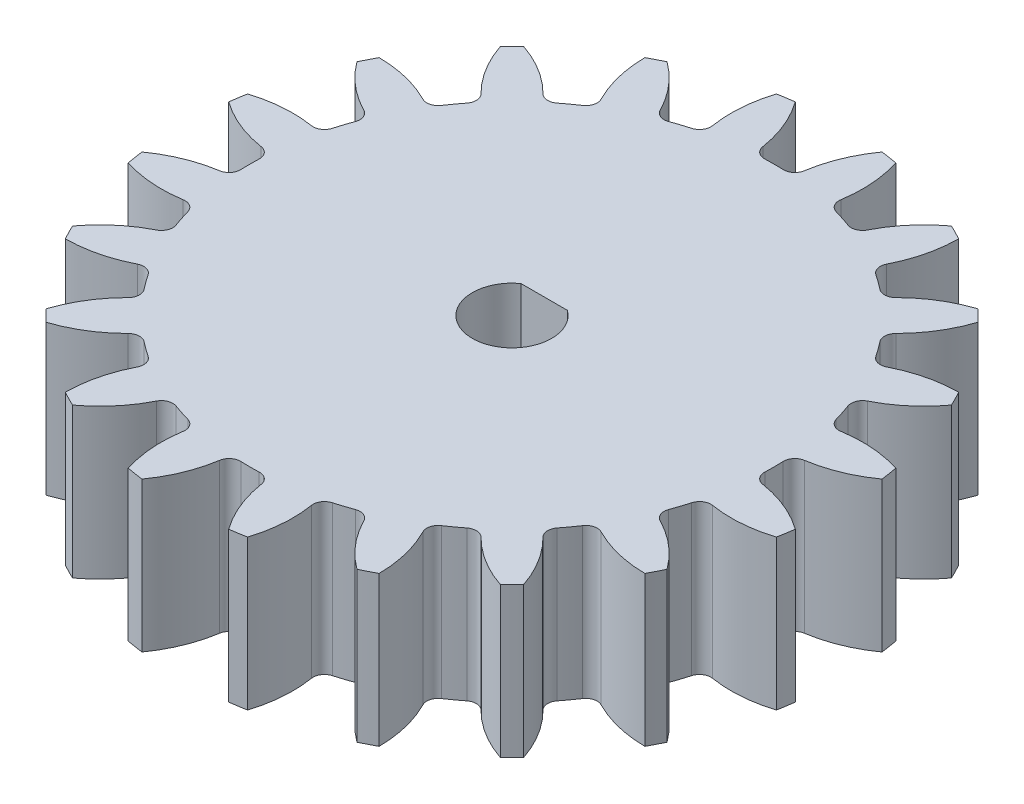
SolidWorks part; units mm, degrees
ref_plane "Front Plane" through (0, 0, 0) normal (0, 0, 1) x (1, 0, 0)
ref_plane "Top Plane" through (0, 0, 0) normal (0, 1, 0) x (1, 0, 0)
ref_plane "Right Plane" through (0, 0, 0) normal (1, 0, 0) x (0, 0, -1)
sketch "Sketch1" plane through (0, 0, 0) normal (0, 1, 0) x (1, 0, 0)
  circle A0 centre (0, 0) radius 2.65
  circle A1 centre (0, 0) radius 22
  dimension "D1" = 5.3
  dimension "D2" = 44
extrude "Boss-Extrude1" add sketch "Sketch1" along normal blind 10
sketch "Sketch2" plane through (0, 10, 0) normal (0, 1, 0) x (1, 0, 0)
  line L0 (0, 0) -> (0, 22) construction
  line L1 (-1.3103, 17.4509) -> (0, 0) construction
  line L2 (0, 14.786) -> (-2.5708, 21.8493) construction
  circle A0 centre (0, 0) radius 22 construction
  arc A1 (1.3103, 17.4509) -> (-1.3103, 17.4509) centre (0, 0) ccw
  arc A2 (1.8681, 19.9126) -> (-1.8681, 19.9126) centre (0, 0) ccw construction
  arc A3 (2.8963, 21.8085) -> (-2.8963, 21.8085) centre (0, 0) ccw
  arc A4 (-2.8963, 21.8085) -> (-1.3103, 17.4509) centre (-9.8515, 16.8096) cw
  arc A5 (2.8963, 21.8085) -> (1.3103, 17.4509) centre (9.8515, 16.8096) ccw
  point P16 (-1.8028, 19.7391)
  dimension "D1" = 44
  dimension "D2" = 40
  dimension "D3" = 4.5
  dimension "D4" = 20
  dimension "D5" = 3.7416
extrude "Cut-Extrude1" cut sketch "Sketch2" against normal through all
fillet "Fillet1" radius 0.76 2 edges at (1.3103, 5, -17.4509) (-1.3103, 5, -17.4509)
pattern_circular "CirPattern2" count 20 over 360 about axis through (0, 0, 0) along (0, 1, 0) of "Cut-Extrude1", "Fillet1"
sketch "Sketch3" plane through (0, 10, 0) normal (0, 1, 0) x (1, 0, 0)
  circle A0 centre (0, 0) radius 20 construction
  dimension "D1" = 40
sketch "Sketch4" plane through (0, 0, 0) normal (0, 1, 0) x (1, 0, 0)
  line L0 (-1.5492, 2.15) -> (1.5492, 2.15)
  arc A0 (1.5492, 2.15) -> (-1.5492, 2.15) centre (0, 0) ccw
  dimension "D2" = 2.65
  dimension "D1" = 2.15
extrude "Boss-Extrude2" add sketch "Sketch4" along normal blind 10
equation "\"Module\"= 2"
equation "\"No. of Teeth\"= 20"
equation "\"Bore Diameter\"= 5.3"
equation "\"Pressure Angle\"= 20deg"
equation "\"Outer Diameter\"= ( \"No. of Teeth\" + 2 ) * \"Module\""
equation "\"Pitch Diameter\"= \"No. of Teeth\" * \"Module\""
equation "\"Backlash\"= 0.3 * \"Module\""
equation "\"Arc Length\"= ( \"Module\" * pi ) / 2 + \"Backlash\""
equation "\"Fillet Radius\"= .38 * \"Module\""
equation "\"Tooth Depth\"= IIF ( \"Module\" <= 1.25 , 2.4 * \"Module\" , 2.25 * \"Module\" )"
equation "\"D1@Sketch1\"=\"Bore Diameter\""
equation "\"D2@Sketch1\"=\"Outer Diameter\""
equation "\"D2@Sketch2\"=\"Pitch Diameter\""
equation "\"D1@Sketch2\"=\"Outer Diameter\""
equation "\"D3@Sketch2\"=\"Tooth Depth\""
equation "\"D4@Sketch2\"=\"Pressure Angle\""
equation "\"D5@Sketch2\"=\"Arc Length\""
equation "\"D1@Fillet1\"=\"Fillet Radius\""
equation "\"D1@CirPattern2\"=\"No. of Teeth\""
equation "\"D1@Sketch3\"=\"Pitch Diameter\""
